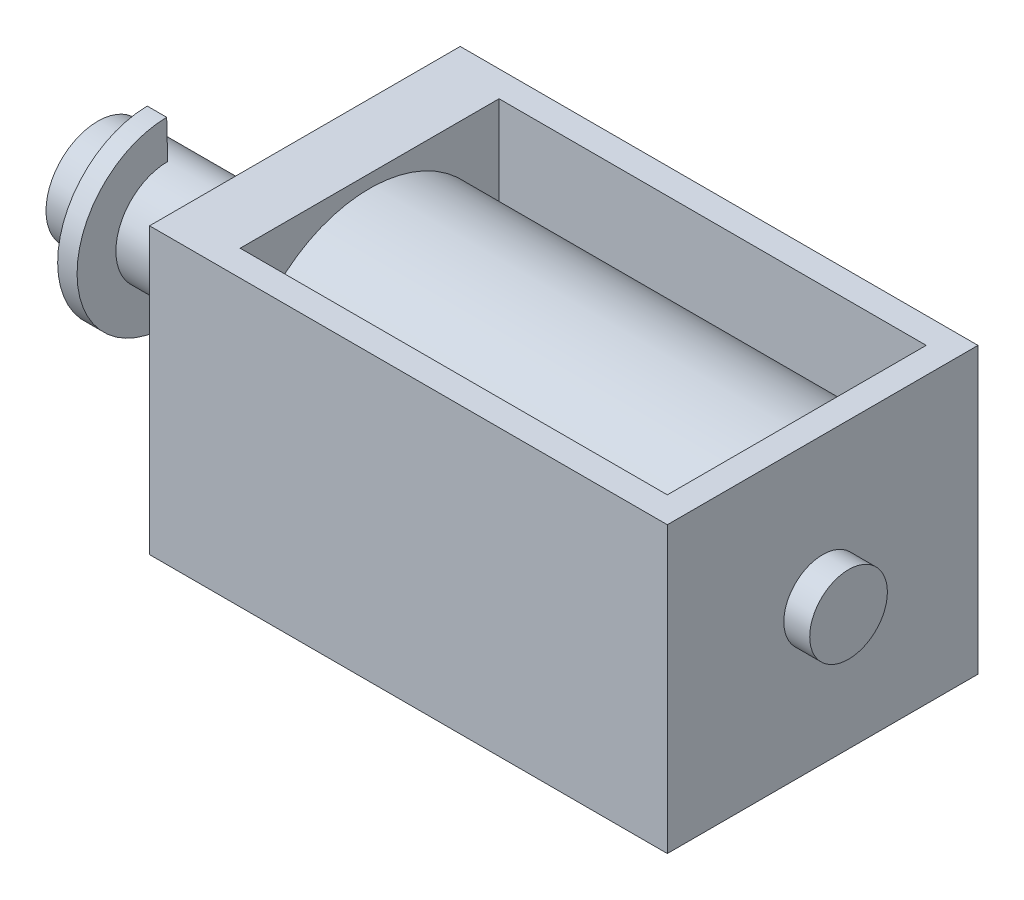
SolidWorks part; units mm, degrees
ref_plane "Front Plane" through (0, 0, 0) normal (0, 0, 1) x (1, 0, 0)
ref_plane "Top Plane" through (0, 0, 0) normal (0, 1, 0) x (1, 0, 0)
ref_plane "Right Plane" through (0, 0, 0) normal (1, 0, 0) x (0, 0, -1)
sketch "Sketch1" plane through (0, 0, 0) normal (0, 1, 0) x (1, 0, 0)
  line L1 (0, 0) -> (20, 0)
  line L2 (0, 0) -> (0, 12)
  line L3 (0, 12) -> (20, 12)
  line L4 (20, 0) -> (20, 12)
  dimension "D1" = 12
  dimension "D2" = 20
extrude "Boss-Extrude1" add sketch "Sketch1" along normal blind 11
sketch "Sketch3" plane through (0, 11, 0) normal (0, 1, 0) x (1, 0, 0)
  line L0 (0, 12) -> (20, 12) construction
  line L1 (2.5, 11) -> (19, 11)
  line L2 (2.5, 11) -> (2.5, 1)
  line L3 (2.5, 1) -> (19, 1)
  line L4 (19, 11) -> (19, 1)
  line L5 (0, 0) -> (20, 0) construction
  line L6 (20, 0) -> (20, 12) construction
  line L7 (0, 12) -> (0, 0) construction
  dimension "D1" = 1
  dimension "D2" = 1
  dimension "D3" = 1
  dimension "D4" = 2.5
extrude "Cut-Extrude1" cut sketch "Sketch3" against normal through all
sketch "Sketch4" plane through (2.5, 0, 0) normal (1, 0, 0) x (0, 0, -1)
  line L0 (6, 11) -> (6, 0) construction
  line L1 (0, 11) -> (12, 11) construction
  line L2 (0, 0) -> (12, 0) construction
  line L3 (11, 0) -> (11, 11) construction
  circle A0 centre (6, 5.5) radius 5
extrude "Boss-Extrude3" add sketch "Sketch4" along normal up to next separate body
sketch "Sketch5" plane through (0, 0, 0) normal (-1, 0, 0) x (0, 0, 1)
  line L0 (-12, 5.5) -> (0, 5.5) construction
  line L1 (-12, 11) -> (-12, 0) construction
  line L2 (0, 11) -> (0, 0) construction
  circle A0 centre (-6, 5.5) radius 2
  dimension "D1" = 4
extrude "Boss-Extrude4" add sketch "Sketch5" along normal blind 8
sketch "Sketch6" plane through (20, 0, 0) normal (1, 0, 0) x (0, 0, -1)
  line L0 (12, 5.5) -> (0, 5.5) construction
  line L1 (12, 11) -> (12, 0) construction
  line L2 (0, 11) -> (0, 0) construction
  circle A0 centre (6, 5.5) radius 1.5
  dimension "D1" = 3
extrude "Boss-Extrude5" add sketch "Sketch6" along normal blind 1
ref_plane "Plane2" through (-5.3, 0, 0) normal (-1, 0, 0) x (0, 0, 1)
sketch "Sketch7" plane through (-5.3, 0, 0) normal (-1, 0, 0) x (0, 0, 1)
  line L0 (-6, 7.5) -> (-5.9615, 8.9998)
  line L1 (-6, 3.5) -> (-6, 2)
  arc A0 (-6, 3.5) -> (-6, 7.5) centre (-6, 5.5) ccw
  circle A1 centre (-6, 5.5) radius 2 construction
  circle A2 centre (-6, 5.5) radius 2 construction
  arc A3 (-6, 2) -> (-5.9615, 8.9998) centre (-6, 5.5) ccw
  dimension "D1" = 3.5
extrude "Boss-Extrude6" add sketch "Sketch7" along normal blind 0.75
